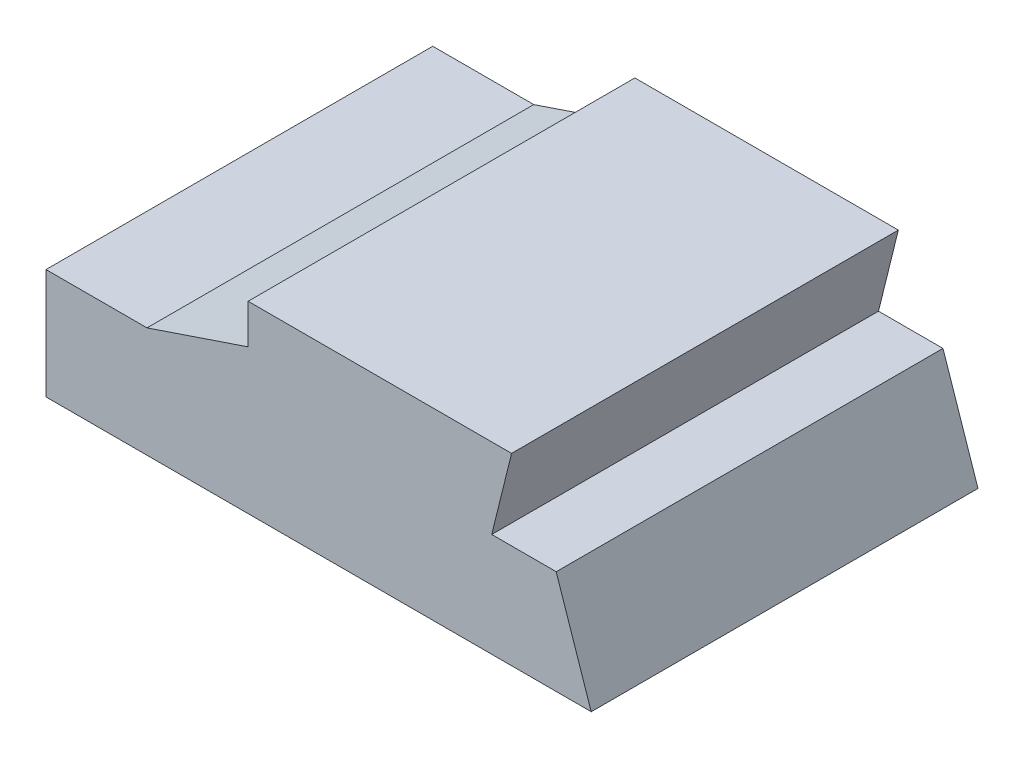
SolidWorks part; units mm, degrees
ref_plane "前视基准面" through (0, 0, 0) normal (0, 0, 1) x (1, 0, 0)
ref_plane "上视基准面" through (0, 0, 0) normal (0, 1, 0) x (1, 0, 0)
ref_plane "右视基准面" through (0, 0, 0) normal (1, 0, 0) x (0, 0, -1)
sketch "草图2" plane through (0, 0, 0) normal (0, 0, 1) x (1, 0, 0)
  line L0 (136.6039, 47.5616) -> (154.1159, 118.2938)
  line L1 (52.2591, 37.348) -> (26.1206, 28.5308)
  line L2 (148.9533, 125.233) -> (88.2808, 128.1975)
  line L3 (0, 28.5308) -> (0, 0)
  line L5 (0, 0) -> (140.98, 0)
  line L6 (26.1206, 28.5308) -> (0, 28.5308)
  line L7 (87.78, 14.3923) -> (87.78, 0) construction
  line L12 (131.9282, 26.834) -> (115.25, 26.834)
  line L13 (120.3818, 47.5616) -> (136.6039, 47.5616)
  line L14 (115.25, 26.834) -> (120.3818, 47.5616)
  line L15 (52.2591, 84.7067) -> (92.2882, 84.7067)
  line L18 (52.2591, 84.7067) -> (52.2591, 37.348)
  line L21 (140.98, 0) -> (131.9282, 26.834)
  line L23 (87.8709, 119.8075) -> (124.18, 103.95) construction
  arc A3 (88.2808, 128.1975) -> (80.8637, 115.1752) centre (87.8709, 119.8075) ccw
  circle A8 centre (124.18, 103.95) radius 27.1849
  arc A11 (92.2882, 84.7067) -> (80.8637, 115.1752) centre (20.1345, 75.0279) ccw
  arc A12 (154.1159, 118.2938) -> (148.9533, 125.233) centre (148.68, 119.6396) ccw
  dimension "D1" = 54.3698
  dimension "D2" = 8.4
  dimension "D3" = 72.8
  dimension "D4" = 5.6
  dimension "D5" = 20.1345
  dimension "D6" = 26.1206
  dimension "D7" = 52.2591
  dimension "D8" = 80.8637
  dimension "D9" = 87.78
  dimension "D10" = 88.2808
  dimension "D11" = 148.68
  dimension "D12" = 92.2882
  dimension "D13" = 115.25
  dimension "D14" = 120.3818
  dimension "D15" = 124.18
  dimension "D16" = 131.9282
  dimension "D17" = 136.6039
  dimension "D18" = 140.98
  dimension "D19" = 26.834
  dimension "D20" = 28.5308
  dimension "D21" = 154.1159
  dimension "D26" = 103.95
extrude "凸台-拉伸1" add sketch "草图2" along normal mid plane 100 contours A11 L15 L18 L1 L6 L3 L5 L21 L12 L14 L13 L0 A8 L2 A3 | L0 A8 L2 | L2 A8 | L0 A12 L2 A8
sketch "草图3" plane through (0, 0, 50) normal (0, 0, 1) x (1, 0, 0)
  line L0 (120.3818, 47.5616) -> (52.2591, 47.5616)
  line L1 (52.2591, 84.7067) -> (52.2591, 37.348) construction
split "分割1" trim tools "草图3" bodies to split 106 resulting bodies 107 108
delete or keep bodies "实体-删除/保留 1" type delete bodies bodies 107
